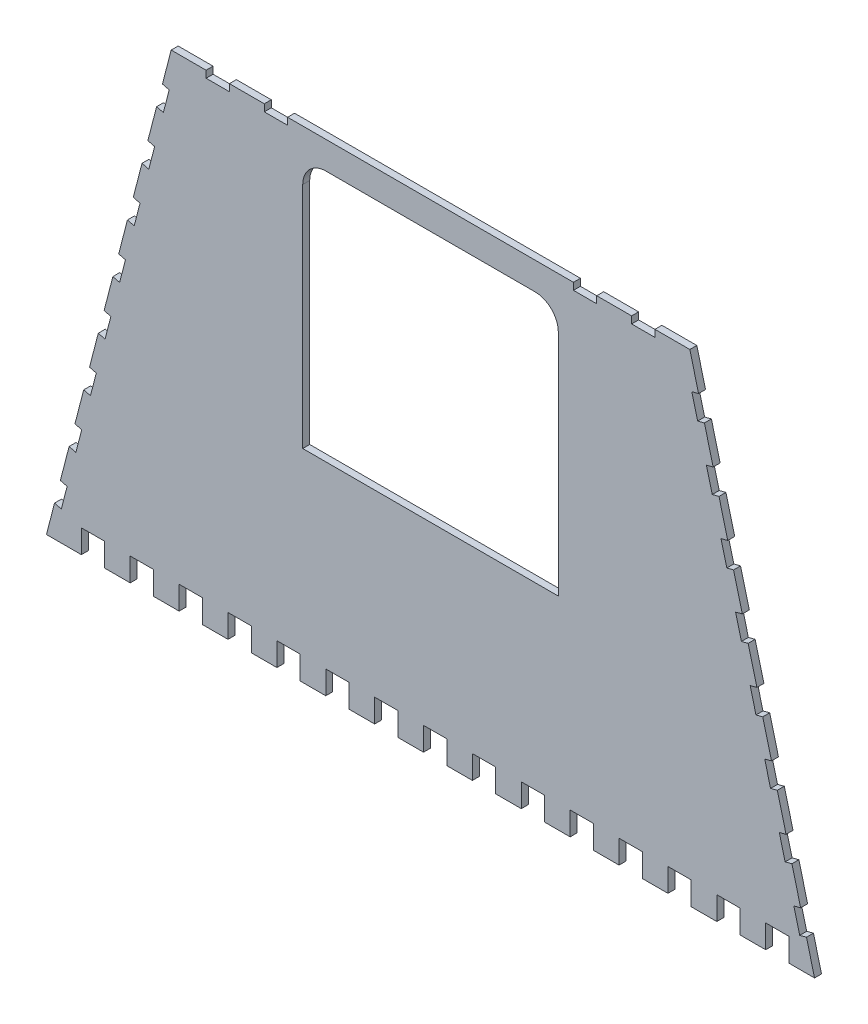
SolidWorks part; units mm, degrees
ref_plane "Front Plane" through (0, 0, 0) normal (0, 0, 1) x (1, 0, 0)
ref_plane "Top Plane" through (0, 0, 0) normal (0, 1, 0) x (1, 0, 0)
ref_plane "Right Plane" through (0, 0, 0) normal (1, 0, 0) x (0, 0, -1)
sketch "Sketch1" plane through (0, 0, 0) normal (0, 0, 1) x (1, 0, 0)
  line L8 (-111.4102, 120) -> (-54.9, 120)
  line L9 (-54.9, 120) -> (-54.9, 0)
  line L10 (-54.9, 0) -> (54.9, 0)
  line L11 (54.9, 0) -> (54.9, 120)
  line L12 (54.9, 120) -> (111.4102, 120)
  line L13 (111.4102, 120) -> (114.8654, 106.6499)
  line L14 (165, -87.0552) -> (-165, -87.0552)
  line L15 (-165, -87.0552) -> (-111.4102, 120)
  line L19 (117.371, 96.9689) -> (165, -87.0552)
  line L20 (121.6671, 120.5926) -> (129.4635, 90.4696)
  line L21 (114.8654, 106.6499) -> (117.371, 96.9689)
  line L22 (54.9, 108.25) -> (-54.9, 108.25)
  line L23 (54.9, 108.25) -> (54.9, 120)
  line L24 (-54.9, 120) -> (-54.9, 108.25)
  point P8 (0, 0)
  point P13 (0, -87.0552)
  dimension "D1" = 56.5102
  dimension "D2" = 109.8
  dimension "D3" = 330
  dimension "D4" = 11.75
  dimension "D5" = 120
  dimension "D6" = 213.8779
  dimension "D7" = 109.8
extrude "Boss-Extrude1" add sketch "Sketch1" along normal blind 3 contours L13 L21 L19 L14 L15 L8 L9 L10 L11 L12
sketch "Sketch3" plane through (0, 0, 3) normal (0, 0, 1) x (1, 0, 0)
  line L0 (115.1686, 105.4785) -> (112.2643, 104.7268)
  line L1 (111.4102, 120) -> (165, -87.0552) construction
  line L2 (112.2643, 104.7268) -> (114.7699, 95.0458)
  line L3 (114.7699, 95.0458) -> (117.6742, 95.7975)
  line L4 (54.9, 120) -> (111.4102, 120) construction
  line L5 (121.4323, 81.2759) -> (118.528, 80.5242)
  line L6 (118.528, 80.5242) -> (121.0337, 70.8432)
  line L7 (121.0337, 70.8432) -> (123.938, 71.5949)
  line L8 (127.6961, 57.0733) -> (124.7918, 56.3216)
  line L9 (124.7918, 56.3216) -> (127.2974, 46.6406)
  line L10 (127.2974, 46.6406) -> (130.2017, 47.3923)
  line L11 (133.9598, 32.8707) -> (131.0555, 32.119)
  line L12 (131.0555, 32.119) -> (133.5611, 22.438)
  line L13 (133.5611, 22.438) -> (136.4654, 23.1897)
  line L14 (140.2235, 8.6681) -> (137.3192, 7.9164)
  line L15 (137.3192, 7.9164) -> (139.8248, -1.7646)
  line L16 (139.8248, -1.7646) -> (142.7291, -1.0129)
  line L17 (146.4872, -15.5345) -> (143.5829, -16.2862)
  line L18 (143.5829, -16.2862) -> (146.0886, -25.9672)
  line L19 (146.0886, -25.9672) -> (148.9929, -25.2155)
  line L20 (152.7509, -39.7371) -> (149.8466, -40.4888)
  line L21 (149.8466, -40.4888) -> (152.3523, -50.1698)
  line L22 (152.3523, -50.1698) -> (155.2566, -49.4181)
  line L23 (159.0147, -63.9397) -> (156.1104, -64.6914)
  line L24 (156.1104, -64.6914) -> (158.616, -74.3724)
  line L25 (158.616, -74.3724) -> (161.5203, -73.6207)
  line L26 (115.1686, 105.4785) -> (121.4323, 81.2759) construction
  dimension "D1" = 3
  dimension "D2" = 10
  dimension "D3" = 165.489
  dimension "D4" = 15
  dimension "D6" = 25
  dimension "D5" = 8
extrude "Cut-Extrude2" cut sketch "Sketch3" against normal blind 3 and the other way through all contours L0 L2 L3
pattern_linear "LPattern2" count 8 spacing 25 along (0.2506, -0.9681, 0) of "Cut-Extrude2"
mirror "Mirror1" about plane through (0, 0, 0) normal (1, 0, 0) of "LPattern2", "Cut-Extrude2"
sketch "Sketch4" plane through (0, 0, 3) normal (0, 0, 1) x (1, 0, 0)
  line L0 (-96.4102, 120) -> (-96.4102, 117)
  line L1 (-111.4102, 120) -> (-54.9, 120) construction
  line L2 (-96.4102, 117) -> (-86.4102, 117)
  line L3 (-86.4102, 117) -> (-86.4102, 120)
  dimension "D1" = 10
  dimension "D2" = 3
extrude "Cut-Extrude3" cut sketch "Sketch4" against normal blind 3 and the other way through all
pattern_linear "LPattern3" count 2 spacing 25 along (1, 0, 0) of "Cut-Extrude3"
mirror "Mirror2" about plane through (0, 0, 0) normal (1, 0, 0) of "LPattern3", "Cut-Extrude3"
sketch "Sketch5" plane through (0, 0, 3) normal (0, 0, 1) x (1, 0, 0)
  line L0 (-150, -87.0552) -> (-150, -77.0552)
  line L1 (165, -87.0552) -> (-165, -87.0552) construction
  line L2 (-150, -77.0552) -> (-140, -77.0552)
  line L3 (-140, -77.0552) -> (-140, -87.0552)
  line L4 (-140, -87.0552) -> (-150, -87.0552)
  dimension "D1" = 10
  dimension "D2" = 10
  dimension "D3" = 15
extrude "Cut-Extrude7" cut sketch "Sketch5" against normal blind 10 contours L0 L2 L3 L4
pattern_linear "LPattern5" count 15 spacing 21 along (1, 0, 0) of "Cut-Extrude7"
ref_plane "Plane1" through (-54.9, 0, 0) normal (0, -1, 0) x (-1, 0, 0)
sketch "Sketch9" plane through (0, 0, 0) normal (0, 0, -1) x (-1, 0, 0)
  line L0 (-54.9, 108.2) -> (54.9, 108.2)
  line L1 (-54.9, 0) -> (-54.9, 120) construction
  line L2 (54.9, 120) -> (54.9, 0) construction
  line L3 (-54.9, 108.2) -> (-54.9, 120)
  line L4 (-54.9, 120) -> (54.9, 120)
  line L5 (54.9, 120) -> (54.9, 108.2)
  dimension "D1" = 11.8
extrude "Boss-Extrude2" add sketch "Sketch9" against normal blind 3
fillet "Fillet1" radius 10 2 edges at (-54.9, 108.2, 1.5) (54.9, 108.2, 1.5)
